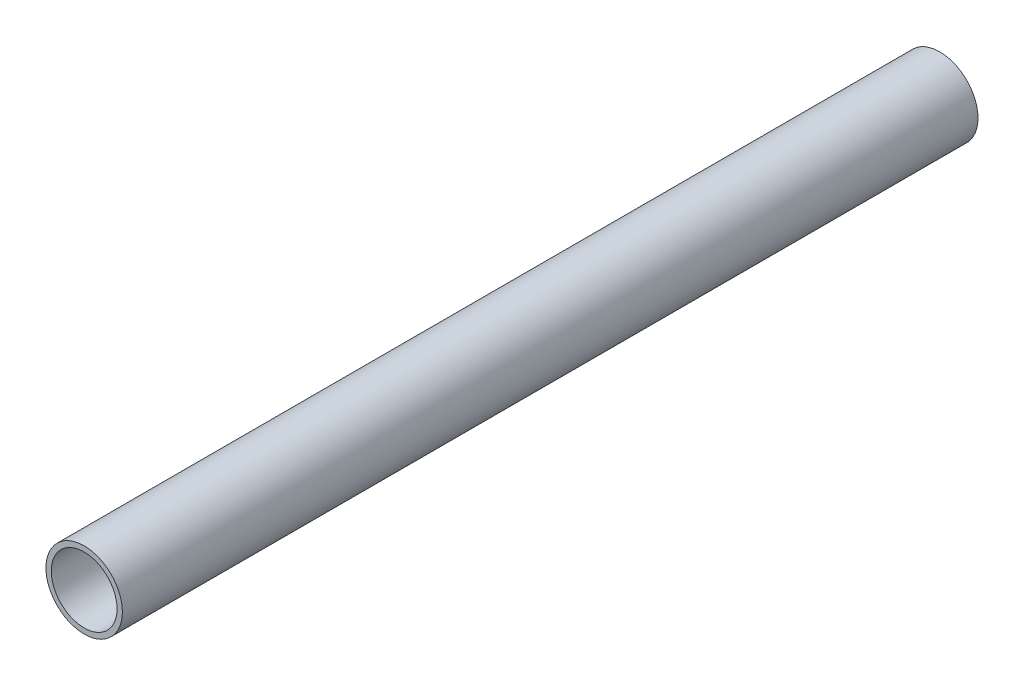
SolidWorks part; units mm, degrees
ref_plane "前视基准面" through (0, 0, 0) normal (0, 0, 1) x (1, 0, 0)
ref_plane "上视基准面" through (0, 0, 0) normal (0, 1, 0) x (1, 0, 0)
ref_plane "右视基准面" through (0, 0, 0) normal (1, 0, 0) x (0, 0, -1)
sketch "草图1" plane through (0, 0, 0) normal (0, 0, 1) x (1, 0, 0)
  circle A0 centre (0, 0) radius 7.55
  circle A1 centre (0, 0) radius 6.5
  dimension "D1" = 15.1
  dimension "D2" = 13
extrude "凸台-拉伸1" add sketch "草图1" along normal blind 169
